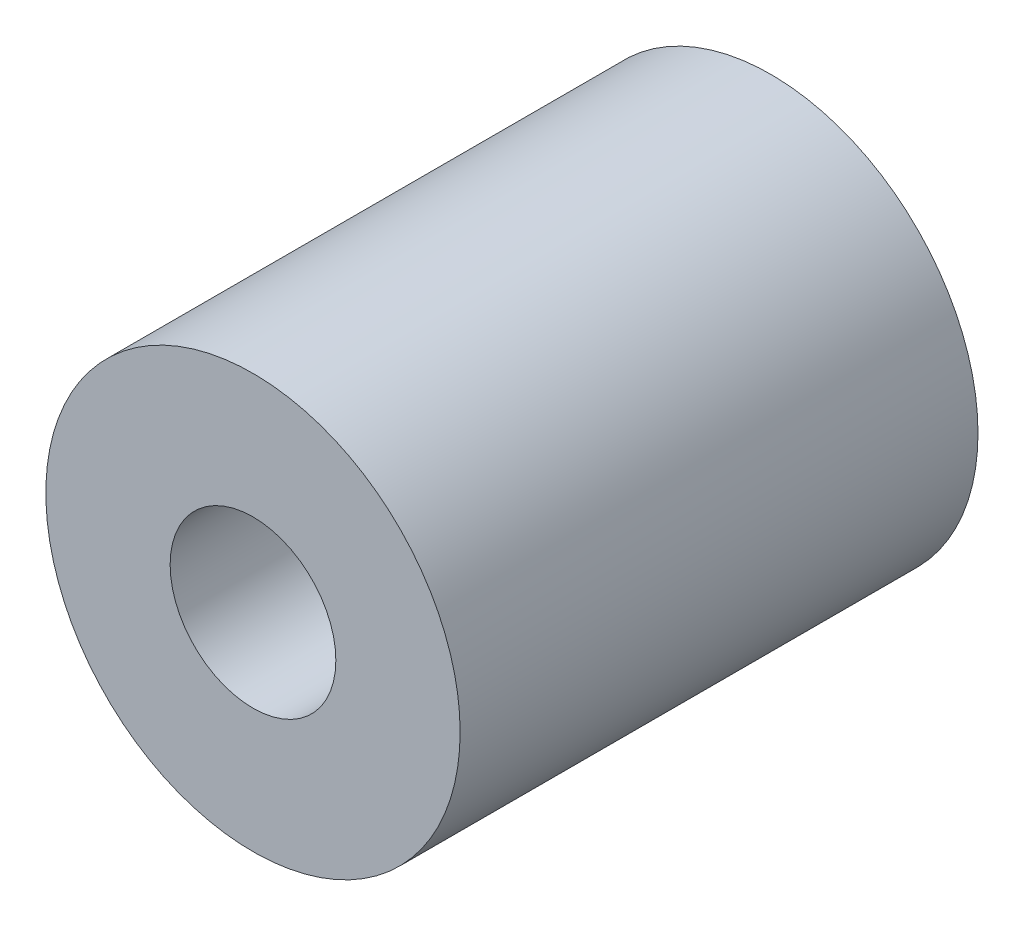
SolidWorks part; units mm, degrees
ref_plane "前视基准面" through (0, 0, 0) normal (0, 0, 1) x (1, 0, 0)
ref_plane "上视基准面" through (0, 0, 0) normal (0, 1, 0) x (1, 0, 0)
ref_plane "右视基准面" through (0, 0, 0) normal (1, 0, 0) x (0, 0, -1)
sketch "草图1" plane through (0, 0, 0) normal (0, 0, 1) x (1, 0, 0)
  circle A0 centre (0, 0) radius 10
  circle A1 centre (0, 0) radius 2
  dimension "D1" = 20
  dimension "D2" = 4
extrude "凸台-拉伸1" add sketch "草图1" along normal blind 12.5
sketch "草图2" plane through (0, 0, 12.5) normal (0, 0, 1) x (1, 0, 0)
  circle A0 centre (0, 0) radius 4
  circle A1 centre (0, 0) radius 10
  circle A2 centre (0, 0) radius 10
  dimension "D2" = 8
  dimension "D1" = 0
extrude "凸台-拉伸2" add sketch "草图2" along normal blind 12.5
